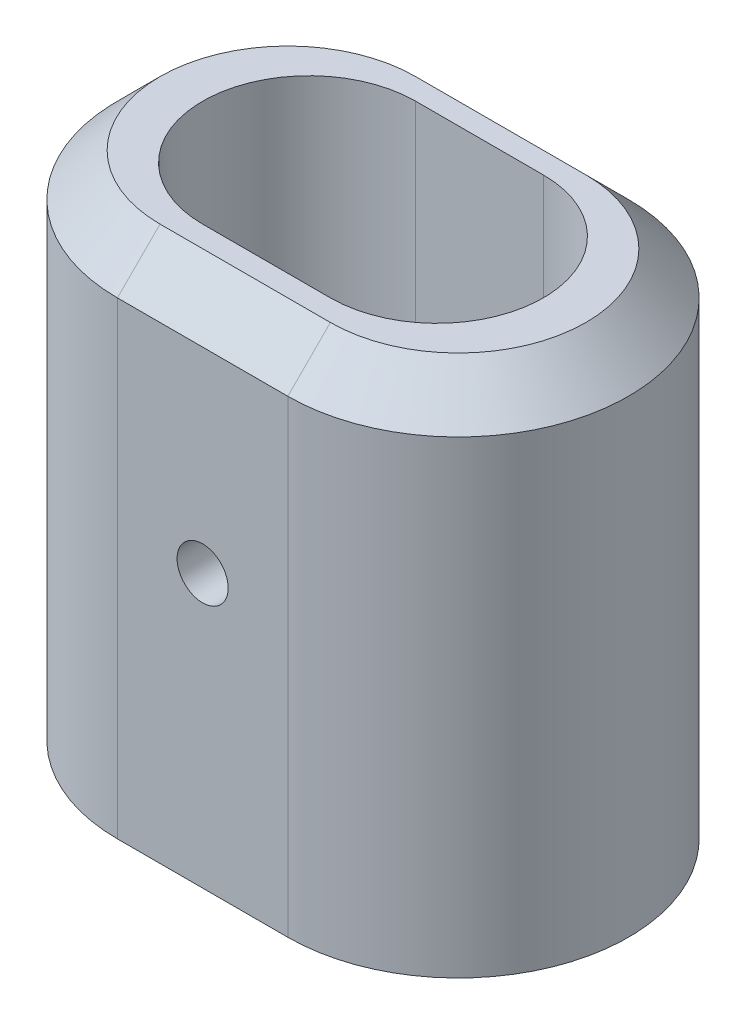
SolidWorks part; units mm, degrees
ref_plane "Front Plane" through (0, 0, 0) normal (0, 0, 1) x (1, 0, 0)
ref_plane "Top Plane" through (0, 0, 0) normal (0, 1, 0) x (1, 0, 0)
ref_plane "Right Plane" through (0, 0, 0) normal (1, 0, 0) x (0, 0, -1)
sketch "Sketch3" plane through (0, 0, 0) normal (0, 1, 0) x (1, 0, 0)
  line L0 (-10, 0) -> (10, 0) construction
  line L1 (-10, 20) -> (10, 20)
  line L2 (-10, -20) -> (10, -20)
  arc A0 (-10, 20) -> (-10, -20) centre (-10, 0) ccw
  arc A1 (10, -20) -> (10, 20) centre (10, 0) ccw
  point P3 (0, 0)
extrude "Boss-Extrude1" add sketch "Sketch3" along normal mid plane 60
sketch "Sketch4" plane through (0, 30, 0) normal (0, 1, 0) x (1, 0, 0)
  line L0 (-7.5, 0) -> (7.5, 0) construction
  line L1 (-7.5, 12.5) -> (7.5, 12.5)
  line L2 (-7.5, -12.5) -> (7.5, -12.5)
  arc A0 (-7.5, 12.5) -> (-7.5, -12.5) centre (-7.5, 0) ccw
  arc A1 (7.5, -12.5) -> (7.5, 12.5) centre (7.5, 0) ccw
  point P2 (0, 0)
extrude "Cut-Extrude1" cut sketch "Sketch4" against normal through all
chamfer "Chamfer1" distance 5 angle 45 4 edges at (0, 30, -20) (-30, 30, 0) (30, 30, 0) (0, 30, 20)
sketch "Sketch5" plane through (0, 0, 20) normal (0, 0, 1) x (1, 0, 0)
  line L0 (-10, 30) -> (10, 30) construction
  line L1 (10, 25) -> (-10, 25) construction
  circle A0 centre (0, 2) radius 3
  point P6 (0, 25)
  dimension "D2" = 6
  dimension "D1" = 28
extrude "Cut-Extrude2" cut sketch "Sketch5" against normal through all
